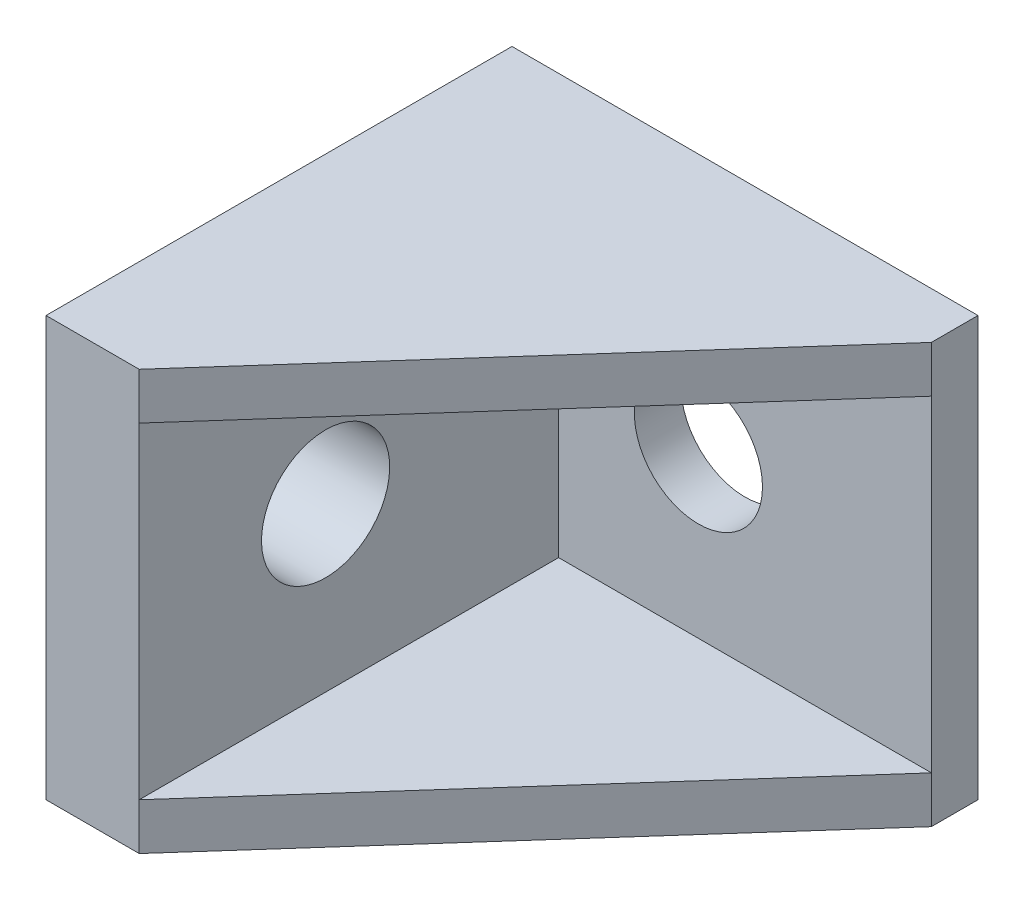
SolidWorks part; units mm, degrees
ref_plane "정면" through (0, 0, 0) normal (0, 0, 1) x (1, 0, 0)
ref_plane "윗면" through (0, 0, 0) normal (0, 1, 0) x (1, 0, 0)
ref_plane "우측면" through (0, 0, 0) normal (1, 0, 0) x (0, 0, -1)
sketch "스케치1" plane through (0, 0, 0) normal (0, 0, 1) x (1, 0, 0)
  line L1 (-10, 9) -> (10, 9)
  line L2 (-10, 9) -> (-10, -9)
  line L3 (-10, -9) -> (10, -9)
  line L4 (10, 9) -> (10, -9)
  line L5 (-10, 9) -> (10, -9) construction
  line L6 (-10, -9) -> (10, 9) construction
  point P0 (0, 0)
  dimension "D1" = 20
  dimension "D2" = 18
extrude "보스-돌출1" add sketch "스케치1" along normal blind 20
sketch "스케치2" plane through (0, 0, 20) normal (0, 0, 1) x (1, 0, 0)
  line L0 (10, -9) -> (10, 9) construction
  line L1 (10, 7) -> (-6, 7)
  line L2 (10, 7) -> (10, -7)
  line L3 (10, -7) -> (-6, -7)
  line L4 (-6, 7) -> (-6, -7)
  line L5 (-10, 9) -> (-10, -9) construction
  line L6 (10, 9) -> (-10, 9) construction
  line L7 (-10, -9) -> (10, -9) construction
  point P10 (0, 9)
  dimension "D1" = 4
  dimension "D2" = 2
  dimension "D3" = 2
extrude "컷-돌출1" cut sketch "스케치2" against normal blind 18
sketch "스케치4" plane through (0, -7, 0) normal (0, 1, 0) x (1, 0, 0)
  line L0 (-6, -20) -> (10, -2)
  line L1 (10, -2) -> (10, -20)
  line L2 (10, -20) -> (-6, -20)
extrude "컷-돌출2" cut sketch "스케치4" against normal through all both and the other way through all
sketch "스케치5" plane through (0, 0, 2) normal (0, 0, 1) x (1, 0, 0)
  line L0 (10, 7) -> (-6, 7) construction
  line L5 (-10, 9) -> (-10, -9) construction
  circle A2 centre (0, 0) radius 2.75
  dimension "D2" = 7
  dimension "D1" = 5.5
  dimension "D3" = 10
extrude "컷-돌출3" cut sketch "스케치5" against normal through all both
sketch "스케치6" plane through (-6, 0, 0) normal (1, 0, 0) x (0, 0, -1)
  line L0 (-2, 7) -> (-20, 7) construction
  line L5 (-20, 7) -> (-20, -7) construction
  circle A2 centre (-12, 0) radius 2.75
  dimension "D2" = 7
  dimension "D1" = 5.5
  dimension "D3" = 8
extrude "컷-돌출4" cut sketch "스케치6" against normal through all both
